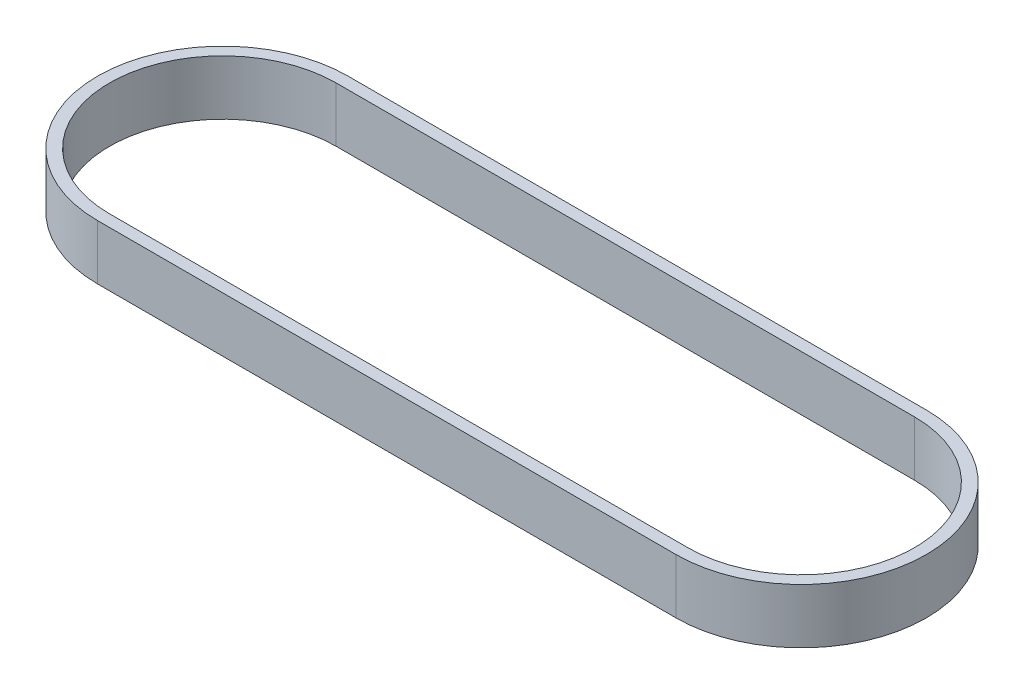
SolidWorks part; units mm, degrees
ref_plane "Front Plane" through (0, 0, 0) normal (0, 0, 1) x (1, 0, 0)
ref_plane "Top Plane" through (0, 0, 0) normal (0, 1, 0) x (1, 0, 0)
ref_plane "Right Plane" through (0, 0, 0) normal (1, 0, 0) x (0, 0, -1)
sketch "Sketch1" plane through (0, 0, 0) normal (0, 1, 0) x (1, 0, 0)
  line L0 (-48.745, 0) -> (49951.255, 0) construction
  line L1 (0, 0) -> (0, 50000) construction
  line L2 (-48.745, 19.1) -> (48.745, 19.1)
  line L3 (-48.745, -19.1) -> (48.745, -19.1)
  line L4 (-48.745, -21.1) -> (48.745, -21.1)
  line L5 (-48.745, 21.1) -> (48.745, 21.1)
  circle A0 centre (-48.745, 0) radius 19.1 construction
  circle A1 centre (48.745, 0) radius 19.1 construction
  arc A2 (-48.745, 19.1) -> (-48.745, -19.1) centre (-48.745, 0) ccw
  arc A3 (48.745, 19.1) -> (48.745, -19.1) centre (48.745, 0) cw
  arc A4 (48.745, 21.1) -> (48.745, -21.1) centre (48.745, 0) cw
  arc A5 (-48.745, 21.1) -> (-48.745, -21.1) centre (-48.745, 0) ccw
  dimension "D2" = 38.2
  dimension "D1" = 97.49
  dimension "D3" = 48.745
  dimension "D4" = 2
extrude "Boss-Extrude1" add sketch "Sketch1" along normal blind 9.25
